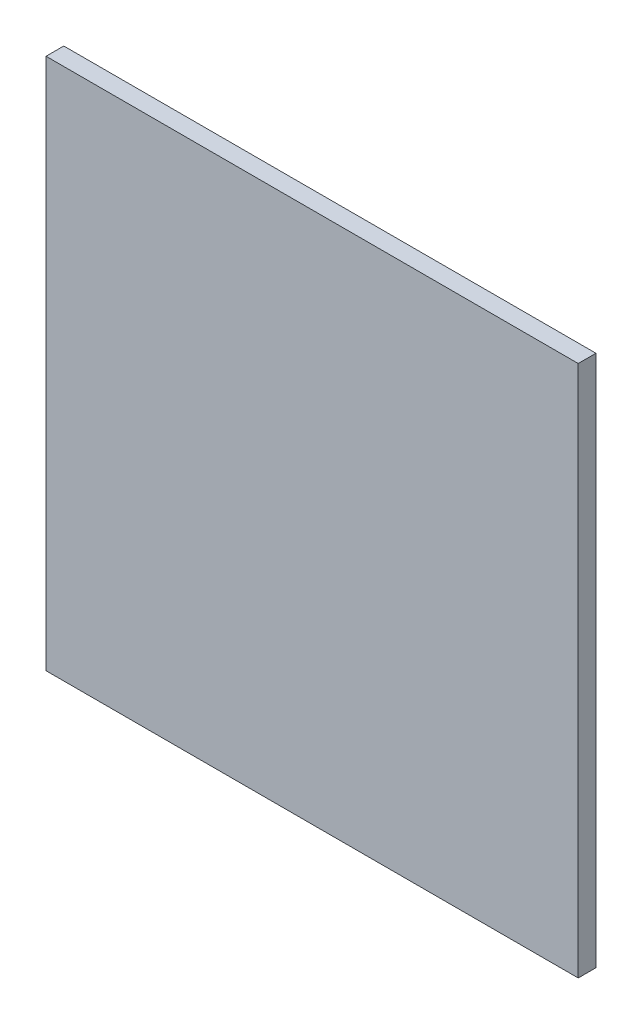
SolidWorks part; units mm, degrees
ref_plane "Front Plane" through (0, 0, 0) normal (0, 0, 1) x (1, 0, 0)
ref_plane "Top Plane" through (0, 0, 0) normal (0, 1, 0) x (1, 0, 0)
ref_plane "Right Plane" through (0, 0, 0) normal (1, 0, 0) x (0, 0, -1)
sketch "Sketch1" plane through (0, 0, 0) normal (0, 0, 1) x (1, 0, 0)
  line L1 (0, 0) -> (76.2, 0)
  line L2 (0, 0) -> (0, 76.2)
  line L3 (0, 76.2) -> (76.2, 76.2)
  line L4 (76.2, 0) -> (76.2, 76.2)
  dimension "D1" = 76.2
  dimension "D2" = 76.2
extrude "Boss-Extrude1" add sketch "Sketch1" along normal blind 2.54
